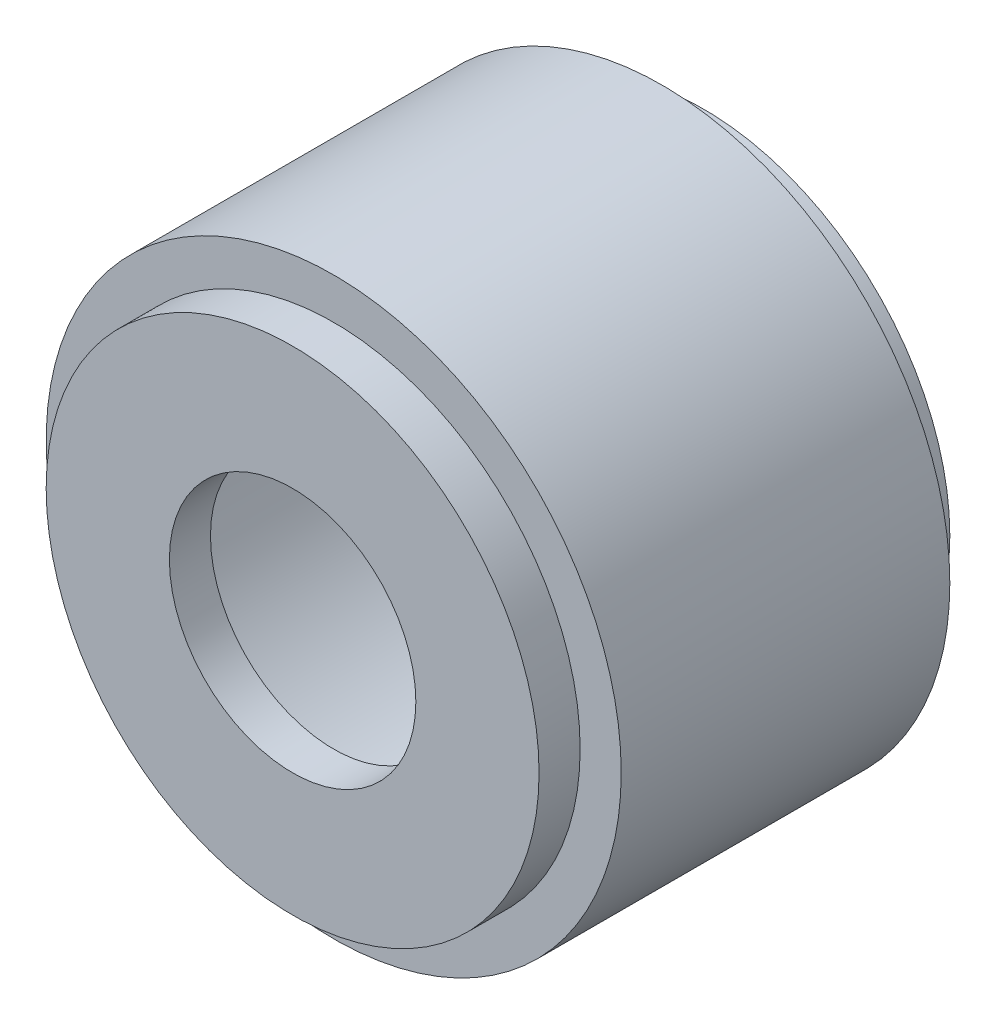
SolidWorks part; units mm, degrees
ref_plane "Alzado" through (0, 0, 0) normal (0, 0, 1) x (1, 0, 0)
ref_plane "Planta" through (0, 0, 0) normal (0, 1, 0) x (1, 0, 0)
ref_plane "Vista lateral" through (0, 0, 0) normal (1, 0, 0) x (0, 0, -1)
sketch "Croquis3" plane through (0, 0, 0) normal (1, 0, 0) x (0, 0, -1)
  line L0 (40, 0) -> (50, 0)
  line L1 (50, 0) -> (50, 60)
  line L2 (50, 60) -> (40, 60)
  line L3 (40, 60) -> (40, 70)
  line L4 (40, 70) -> (-40, 70)
  line L5 (-40, 70) -> (-40, 60)
  line L6 (-40, 60) -> (-50, 60)
  line L7 (-50, 60) -> (-50, 30)
  line L8 (-50, 30) -> (-40, 30)
  line L9 (-40, 30) -> (-40, 50)
  line L10 (-40, 50) -> (-30, 50)
  line L11 (-30, 50) -> (-30, 60)
  line L12 (-30, 60) -> (30, 60)
  line L13 (30, 60) -> (30, 50)
  line L14 (30, 50) -> (40, 50)
  line L15 (40, 50) -> (40, 0)
  line L16 (-147.0349, 0) -> (160.7438, 0) construction
  point P18 (0, 60)
  point P19 (45, 0)
  point P20 (-35, 50)
  dimension "D1" = 10
  dimension "D2" = 10
  dimension "D3" = 80
  dimension "D4" = 10
  dimension "D5" = 10
  dimension "D6" = 30
  dimension "D7" = 50
  dimension "D8" = 60
  dimension "D9" = 70
revolve "Revolución1" add sketch "Croquis3" angle 360 about L16
